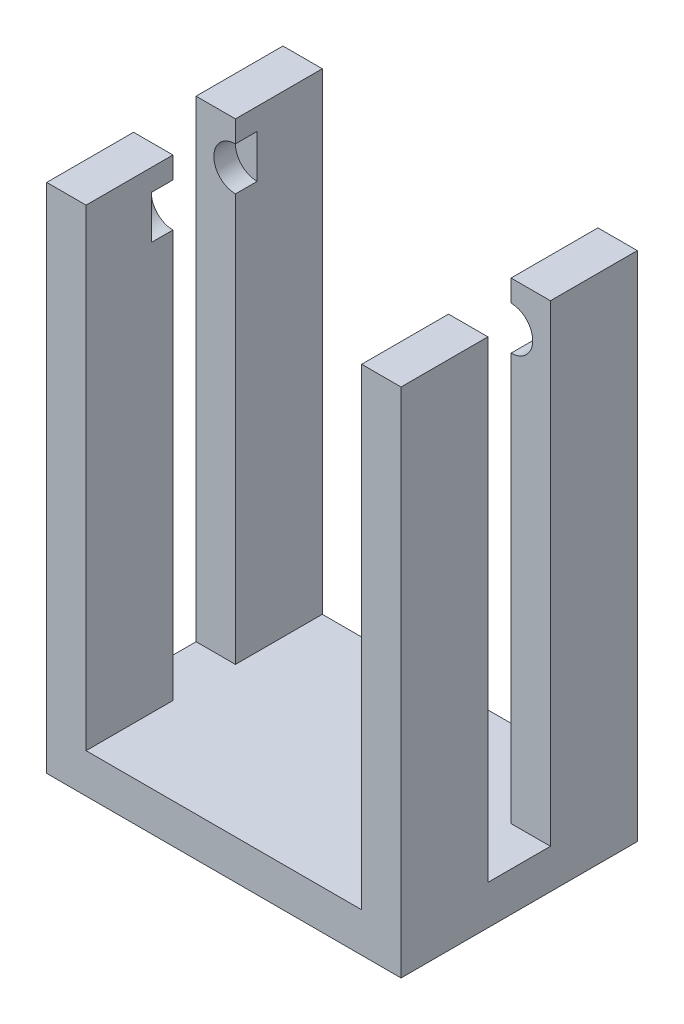
SolidWorks part; units mm, degrees
ref_plane "前基準面" through (0, 0, 0) normal (0, 0, 1) x (1, 0, 0)
ref_plane "上基準面" through (0, 0, 0) normal (0, 1, 0) x (1, 0, 0)
ref_plane "右基準面" through (0, 0, 0) normal (1, 0, 0) x (0, 0, -1)
sketch "草圖1" plane through (0, 0, 0) normal (0, 1, 0) x (1, 0, 0)
  line L1 (-4.5, 3) -> (4.5, 3)
  line L2 (-4.5, 3) -> (-4.5, -3)
  line L3 (-4.5, -3) -> (4.5, -3)
  line L4 (4.5, 3) -> (4.5, -3)
  line L5 (-4.5, 3) -> (4.5, -3) construction
  line L6 (-4.5, -3) -> (4.5, 3) construction
  point P0 (0, 0)
  dimension "D1" = 9
  dimension "D2" = 6
extrude "填料-伸長1" add sketch "草圖1" along normal blind 1
sketch "草圖2" plane through (0, 1, 0) normal (0, 1, 0) x (1, 0, 0)
  line L0 (-3.15, 0) -> (3.15, 0)
  line L2 (-4.5, -3) -> (4.5, -3) construction
  line L3 (3.15, 0) -> (3.15, -3) construction
  line L4 (3.15, -3) -> (3.15, 3) construction
  line L5 (4.5, 3) -> (-4.5, 3) construction
  line L6 (-4.5, 0.7938) -> (-4.5, -0.7938)
  line L7 (-4.5, 3) -> (-4.5, -3) construction
  line L8 (-4.5, 0.7938) -> (-3.5, 0.7938)
  line L9 (-3.5, 0.7938) -> (-3.5, 3)
  line L10 (-3.5, 3) -> (-4.5, 3)
  line L11 (-4.5, 3) -> (-4.5, 0.7938)
  line L12 (-4.5, -0.7938) -> (-3.5, -0.7938)
  line L13 (-3.5, -0.7938) -> (-3.5, -3)
  line L14 (-3.5, -3) -> (-4.5, -3)
  line L15 (-4.5, -3) -> (-4.5, -0.7938)
  line L16 (4.5, 0.7938) -> (4.5, -0.7938)
  line L17 (4.5, -3) -> (4.5, 3) construction
  line L18 (4.5, 0.7938) -> (3.5, 0.7938)
  line L19 (3.5, 0.7938) -> (3.5, 3)
  line L20 (3.5, 3) -> (4.5, 3)
  line L21 (4.5, 3) -> (4.5, 0.7938)
  line L22 (4.5, -0.7938) -> (3.5, -0.7938)
  line L23 (3.5, -0.7938) -> (3.5, -3)
  line L24 (3.5, -3) -> (4.5, -3)
  line L25 (4.5, -3) -> (4.5, -0.7938)
  point P4 (0, 0)
  point P10 (-3.15, 0)
  point P18 (-4.5, 0)
  point P31 (4.5, 0)
  line M4 (4.5, -3) -> (4.5, 3)
  line M5 (4.5, 3) -> (-4.5, 3)
  line M6 (-4.5, 3) -> (-4.5, -3)
  line M7 (-4.5, -3) -> (4.5, -3)
extrude "填料-伸長2" add sketch "草圖2" along normal blind 12 contours L8 L9 M5 M6 | L13 L12 M6 M7 | L22 L23 M7 M4 | L19 L18 M4 M5
sketch "草圖4" plane through (0, 0, -0.7938) normal (0, 0, 1) x (1, 0, 0)
  line L0 (3.5, 13) -> (3.5, 11.8975)
  line L1 (3.5, 13) -> (3.5, 1) construction
  circle A0 centre (3.5, 11.8975) radius 0.55
  line M4 (3.5, 13) -> (3.5, 1)
extrude "除料-伸長1" cut sketch "草圖4" against normal blind 0.55 contours A0 L0 M4
sketch "草圖6" plane through (0, 0, 0.7938) normal (0, 0, -1) x (-1, 0, 0)
  line L0 (-3.5, 13) -> (-3.5, 11.9)
  line L1 (-3.5, 13) -> (-3.5, 1) construction
  circle A0 centre (-3.5, 11.9) radius 0.55
  line M2 (-3.5, 1) -> (-3.5, 13)
extrude "除料-伸長2" cut sketch "草圖6" against normal blind 0.55 contours A0 M2
sketch "草圖7" plane through (0, 0, 0.7938) normal (0, 0, -1) x (-1, 0, 0)
  line L0 (3.5, 13) -> (3.5, 11.9)
  line L1 (3.5, 13) -> (3.5, 1) construction
  circle A0 centre (3.5, 11.9) radius 0.55
  line M5 (3.5, 13) -> (3.5, 1)
extrude "除料-伸長3" cut sketch "草圖7" against normal blind 0.55 contours A0 L0 M5
sketch "草圖8" plane through (0, 0, -0.7938) normal (0, 0, 1) x (1, 0, 0)
  line L0 (-3.5, 13) -> (-3.5, 11.9)
  line L1 (-3.5, 13) -> (-3.5, 1) construction
  circle A0 centre (-3.5, 11.9) radius 0.55
  line M3 (-3.5, 1) -> (-3.5, 13)
extrude "除料-伸長4" cut sketch "草圖8" against normal blind 0.55 contours A0 M3
